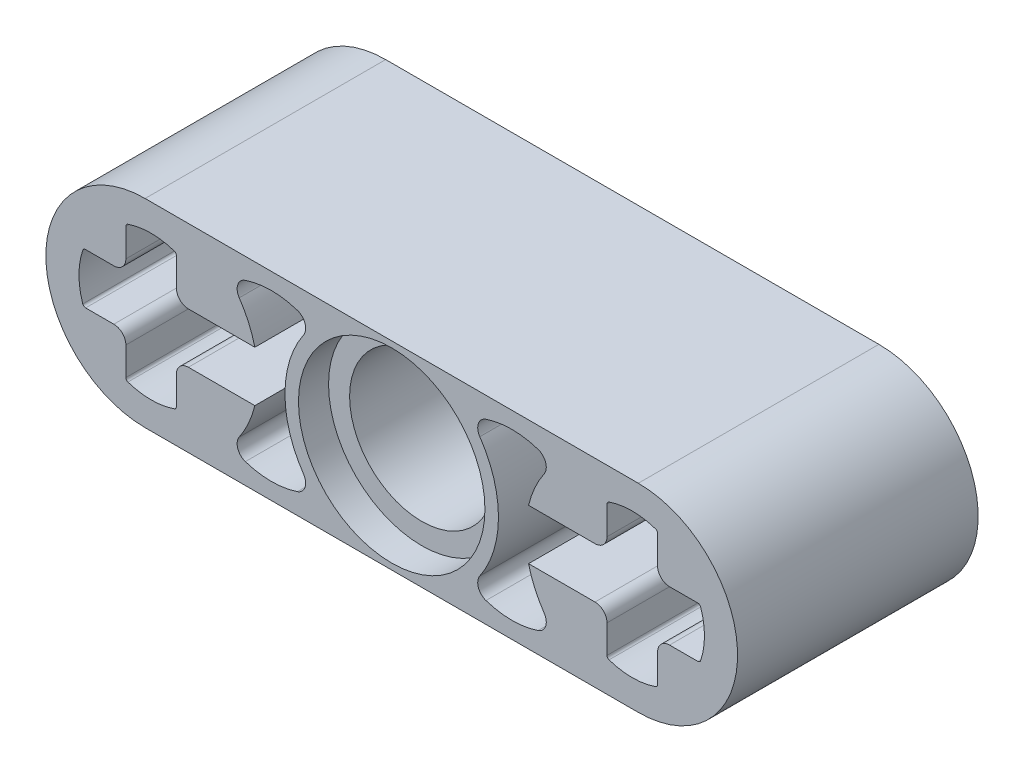
SolidWorks part; units mm, degrees
ref_plane "Front Plane" through (0, 0, 0) normal (0, 0, 1) x (1, 0, 0)
ref_plane "Top Plane" through (0, 0, 0) normal (0, 1, 0) x (1, 0, 0)
ref_plane "Right Plane" through (0, 0, 0) normal (1, 0, 0) x (0, 0, -1)
sketch "Sketch2" plane through (0, 0, 0) normal (0, 0, 1) x (1, 0, 0)
  line L1 (-9.24, 0.84) -> (-10.1777, 0.84)
  line L2 (-8.84, -2.1777) -> (-8.84, -1.24)
  line L3 (-7.16, -2.1777) -> (-7.16, -1.24)
  line L4 (-5.8223, 0.84) -> (-6.76, 0.84)
  line L5 (-5.8223, -0.84) -> (-6.76, -0.84)
  line L6 (-8.84, 1.24) -> (-8.84, 2.1777)
  line L7 (-7.16, 1.24) -> (-7.16, 2.1777)
  line L8 (-9.24, -0.84) -> (-10.1777, -0.84)
  line L9 (-5.7518, 0.84) -> (-4.5508, 0.84)
  line L10 (-5.7518, -0.84) -> (-4.5508, -0.84)
  line L11 (-5.8223, -0.84) -> (-5.7518, -0.84)
  line L12 (-5.8223, 0.84) -> (-5.7518, 0.84)
  line L13 (0, -3.63) -> (0, 3.63) construction
  line L14 (8.84, 1.24) -> (8.84, 2.1777)
  line L15 (7.16, 1.24) -> (7.16, 2.1777)
  line L16 (5.8223, 0.84) -> (6.76, 0.84)
  line L17 (5.8223, 0.84) -> (5.7518, 0.84)
  line L18 (5.7518, 0.84) -> (4.5508, 0.84)
  line L19 (5.7518, -0.84) -> (4.5508, -0.84)
  line L20 (5.8223, -0.84) -> (5.7518, -0.84)
  line L21 (5.8223, -0.84) -> (6.76, -0.84)
  line L22 (7.16, -2.1777) -> (7.16, -1.24)
  line L23 (8.84, -2.1777) -> (8.84, -1.24)
  line L24 (9.24, -0.84) -> (10.1777, -0.84)
  line L25 (9.24, 0.84) -> (10.1777, 0.84)
  line L27 (-8.2, 3.3) -> (8.2, 3.3)
  line L28 (-8.2, -3.3) -> (8.2, -3.3)
  circle A0 centre (0, 0) radius 2.4
  arc A1 (-4.866, -2.6101) -> (-3.134, -2.6101) centre (-4, 0) ccw
  arc A2 (-2.9299, -2.0046) -> (-3.134, -2.6101) centre (-3.26, -2.2304) cw
  arc A3 (-2.9299, -2.0046) -> (-2.9299, 2.0046) centre (0, 0) cw
  arc A4 (-2.9299, 2.0046) -> (-3.134, 2.6101) centre (-3.26, 2.2304) ccw
  arc A5 (-3.134, 2.6101) -> (-4.866, 2.6101) centre (-4, 0) ccw
  arc A6 (-5.0701, 2.0046) -> (-4.866, 2.6101) centre (-4.74, 2.2304) cw
  arc A7 (-5.0701, -2.0046) -> (-5.0701, 2.0046) centre (-8, 0) ccw
  arc A8 (-5.0701, -2.0046) -> (-4.866, -2.6101) centre (-4.74, -2.2304) ccw
  arc A9 (-7.2278, 2.2724) -> (-8.7722, 2.2724) centre (-8, 0) ccw
  arc A10 (-10.2724, 0.7722) -> (-10.2724, -0.7722) centre (-8, 0) ccw
  arc A11 (-8.7722, -2.2724) -> (-7.2278, -2.2724) centre (-8, 0) ccw
  arc A12 (-8.84, -1.24) -> (-9.24, -0.84) centre (-9.24, -1.24) ccw
  arc A13 (-7.16, -1.24) -> (-6.76, -0.84) centre (-6.76, -1.24) cw
  arc A14 (-6.76, 0.84) -> (-7.16, 1.24) centre (-6.76, 1.24) cw
  arc A15 (-9.24, 0.84) -> (-8.84, 1.24) centre (-9.24, 1.24) ccw
  arc A16 (-10.1777, 0.84) -> (-10.2724, 0.7722) centre (-10.1777, 0.74) ccw
  arc A17 (-10.1777, -0.84) -> (-10.2724, -0.7722) centre (-10.1777, -0.74) cw
  arc A18 (-8.7722, -2.2724) -> (-8.84, -2.1777) centre (-8.74, -2.1777) cw
  arc A19 (-7.2278, -2.2724) -> (-7.16, -2.1777) centre (-7.26, -2.1777) ccw
  arc A20 (-7.2278, 2.2724) -> (-7.16, 2.1777) centre (-7.26, 2.1777) cw
  arc A21 (-8.84, 2.1777) -> (-8.7722, 2.2724) centre (-8.74, 2.1777) cw
  arc A22 (-4.5508, -0.84) -> (-4.5508, 0.84) centre (-8, 0) ccw
  arc A31 (5.0701, -2.0046) -> (4.866, -2.6101) centre (4.74, -2.2304) cw
  arc A32 (5.0701, -2.0046) -> (5.0701, 2.0046) centre (8, 0) cw
  arc A33 (5.0701, 2.0046) -> (4.866, 2.6101) centre (4.74, 2.2304) ccw
  arc A34 (3.134, 2.6101) -> (4.866, 2.6101) centre (4, 0) cw
  arc A35 (2.9299, 2.0046) -> (3.134, 2.6101) centre (3.26, 2.2304) cw
  arc A36 (2.9299, -2.0046) -> (2.9299, 2.0046) centre (0, 0) ccw
  arc A37 (2.9299, -2.0046) -> (3.134, -2.6101) centre (3.26, -2.2304) ccw
  arc A38 (4.866, -2.6101) -> (3.134, -2.6101) centre (4, 0) cw
  arc A39 (9.24, 0.84) -> (8.84, 1.24) centre (9.24, 1.24) cw
  arc A40 (8.84, 2.1777) -> (8.7722, 2.2724) centre (8.74, 2.1777) ccw
  arc A41 (7.2278, 2.2724) -> (8.7722, 2.2724) centre (8, 0) cw
  arc A42 (7.2278, 2.2724) -> (7.16, 2.1777) centre (7.26, 2.1777) ccw
  arc A43 (6.76, 0.84) -> (7.16, 1.24) centre (6.76, 1.24) ccw
  arc A44 (4.5508, -0.84) -> (4.5508, 0.84) centre (8, 0) cw
  arc A45 (7.16, -1.24) -> (6.76, -0.84) centre (6.76, -1.24) ccw
  arc A46 (7.2278, -2.2724) -> (7.16, -2.1777) centre (7.26, -2.1777) cw
  arc A47 (8.7722, -2.2724) -> (7.2278, -2.2724) centre (8, 0) cw
  arc A48 (8.7722, -2.2724) -> (8.84, -2.1777) centre (8.74, -2.1777) ccw
  arc A49 (8.84, -1.24) -> (9.24, -0.84) centre (9.24, -1.24) cw
  arc A50 (10.1777, -0.84) -> (10.2724, -0.7722) centre (10.1777, -0.74) ccw
  arc A51 (10.2724, 0.7722) -> (10.2724, -0.7722) centre (8, 0) cw
  arc A52 (10.1777, 0.84) -> (10.2724, 0.7722) centre (10.1777, 0.74) cw
  arc A56 (-8.2, 3.3) -> (-8.2, -3.3) centre (-8.2, 0) ccw
  arc A57 (8.2, 3.3) -> (8.2, -3.3) centre (8.2, 0) cw
  point P115 (0, 3.3)
  point P118 (0, -3.3)
  dimension "D1" = 4.8
  dimension "D2" = 4
  dimension "D3" = 8
extrude "Boss-Extrude1" add sketch "Sketch2" along normal mid plane 8 contours A57 L27 A56 L28 A0 L6 A21 A9 A20 L7 A14 L4 L12 L9 A7 A6 A5 A4 A3 A2 A1 A8 L10 L11 L5 A13 L3 A19 A11 A18 L2 A12 L8 A17 A10 A16 L1 A15 L25 A52 A51 A50 L24 A49 L23 A48 A47
sketch "Sketch4" plane through (0, 0, 4) normal (0, 0, 1) x (1, 0, 0)
  circle A0 centre (0, 0) radius 3.1
  dimension "D1" = 6.2
extrude "Cut-Extrude1" cut sketch "Sketch4" against normal blind 1 contours A0
mirror "Mirror1" about plane through (0, 0, 0) normal (0, 0, 1) of "Cut-Extrude1"
